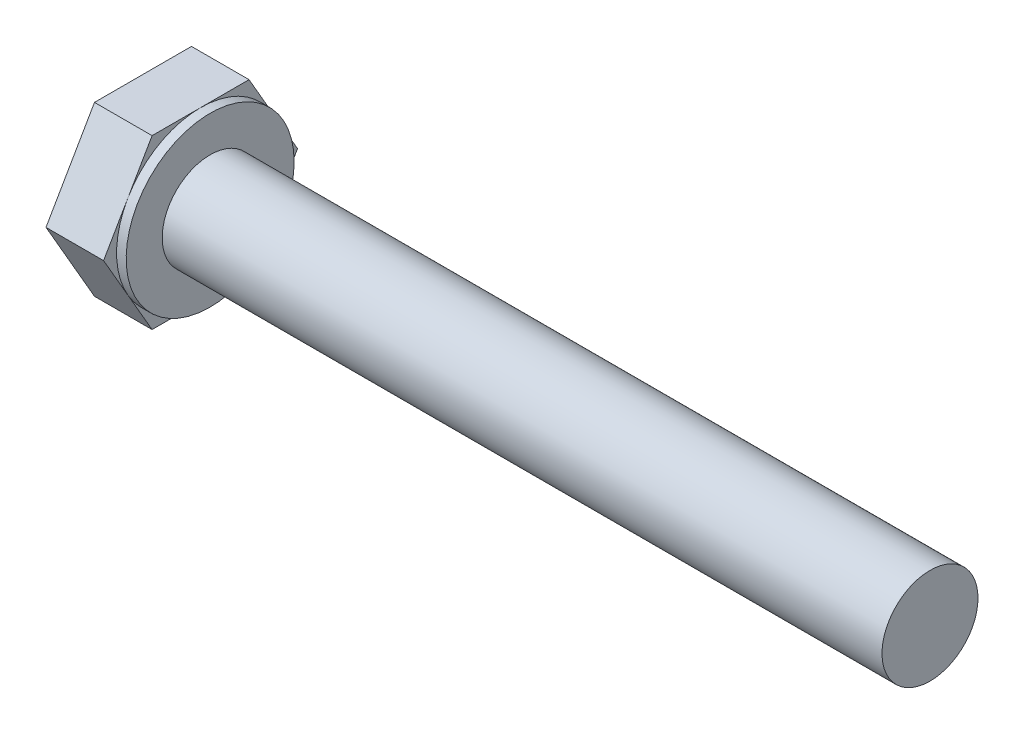
SolidWorks part; units mm, degrees
material "Plain Carbon Steel"
ref_plane "Front Plane" through (0, 0, 0) normal (0, 0, 1) x (1, 0, 0)
ref_plane "Top Plane" through (0, 0, 0) normal (0, 1, 0) x (1, 0, 0)
ref_plane "Right Plane" through (0, 0, 0) normal (1, 0, 0) x (0, 0, -1)
sketch "Sketch1" plane through (0, 0, 0) normal (1, 0, 0) x (0, 0, -1)
  line L1 (-4.0415, 0) -> (-2.0207, -3.5)
  line L2 (-2.0207, -3.5) -> (2.0207, -3.5)
  line L3 (2.0207, -3.5) -> (4.0415, 0)
  line L4 (4.0415, 0) -> (2.0207, 3.5)
  line L5 (2.0207, 3.5) -> (-2.0207, 3.5)
  line L6 (-2.0207, 3.5) -> (-4.0415, 0)
  circle A0 centre (0, 0) radius 3.5 construction
  dimension "D1" = 7
extrude "Boss-Extrude1" add sketch "Sketch1" against normal blind 2.4
sketch "Sketch2" plane through (0, 0, 0) normal (1, 0, 0) x (0, 0, -1)
  line L0 (2.0207, 3.5) -> (-2.0207, 3.5) construction
  circle A0 centre (0, 0) radius 3.5
extrude "Boss-Extrude2" add sketch "Sketch2" along normal blind 0.4
sketch "Sketch3" plane through (0.4, 0, 0) normal (1, 0, 0) x (0, 0, -1)
  circle A0 centre (0, 0) radius 2
  dimension "D1" = 4
extrude "Boss-Extrude3" add sketch "Sketch3" along normal blind 30
